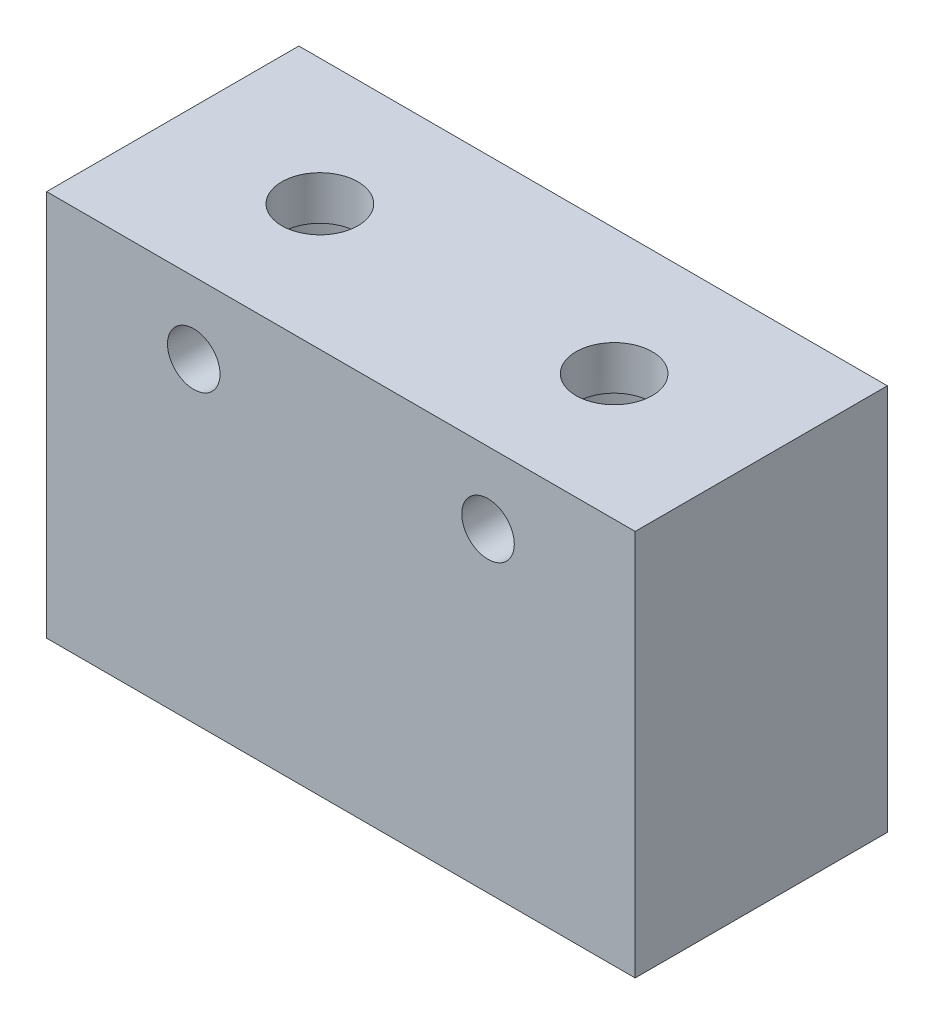
SolidWorks part; units mm, degrees
material "6061 Alloy"
ref_plane "Front Plane" through (0, 0, 0) normal (0, 0, 1) x (1, 0, 0)
ref_plane "Top Plane" through (0, 0, 0) normal (0, 1, 0) x (1, 0, 0)
ref_plane "Right Plane" through (0, 0, 0) normal (1, 0, 0) x (0, 0, -1)
sketch "Sketch1" plane through (0, 0, 0) normal (0, 1, 0) x (1, 0, 0)
  line L1 (-44.45, -19.05) -> (44.45, -19.05)
  line L2 (-44.45, -19.05) -> (-44.45, 19.05)
  line L3 (-44.45, 19.05) -> (44.45, 19.05)
  line L4 (44.45, -19.05) -> (44.45, 19.05)
  line L5 (-44.45, -19.05) -> (44.45, 19.05) construction
  line L6 (-44.45, 19.05) -> (44.45, -19.05) construction
  point P0 (0, 0)
  dimension "D1" = 88.9
  dimension "D2" = 38.1
extrude "Block" add sketch "Sketch1" along normal blind 58.42
sketch "Sketch4" plane through (0, 0, 0) normal (0, -1, 0) x (1, 0, 0)
  line L0 (-22.225, 0) -> (22.225, 0) construction
  point P0 (-22.225, 0)
  point P1 (22.225, 0)
  dimension "D1" = 44.45
hole_wizard "Spring Bores" positions "Sketch6" profile "Sketch7" hole size "1" standard "ANSI Inch"
sketch "Sketch6" plane through (0, 0, 0) normal (0, -1, 0) x (-1, 0, 0)
  point P0 (22.225, 0)
  point P2 (-22.225, 0)
sketch "Sketch7" plane through (-22.225, 0, 0) normal (1, 0, 0) x (0, 0, -1)
  line L0 (0, 0) -> (0, 55.2559)
  line L1 (0, 55.2559) -> (12.7, 47.625)
  line L2 (12.7, 47.625) -> (12.7, 0)
  line L5 (12.7, 0) -> (0, 0)
  line L10 (0, 55.2559) -> (-12.7, 47.625) construction
  line L11 (0, -6.35) -> (0, 107.95) construction
  dimension "Hole Dia." = 25.4
  dimension "Hole Depth" = 47.625
  dimension "Drill Angle" = 118
hole_wizard "1/2-20 Tapped Holes" positions "Sketch9" profile "Sketch8" tap size "1/2-20" standard "ANSI Inch" end condition through all
sketch "Sketch9" plane through (0, 58.42, 0) normal (0, 1, 0) x (1, 0, 0)
  point P0 (-22.225, 0)
  point P3 (22.225, 0)
sketch "Sketch8" plane through (-22.225, 58.42, 0) normal (1, 0, 0) x (0, 0, 1)
  line L0 (0, 0) -> (0, 58.42)
  line L1 (0, 58.42) -> (5.7544, 58.42)
  line L2 (5.7544, 58.42) -> (5.7544, 0)
  line L5 (5.7544, 0) -> (0, 0)
  line L11 (0, -6.35) -> (0, 107.95) construction
  dimension "Thread Major Dia." = 11.5087
  dimension "Thru Tap Drill Depth" = 58.42
hole_wizard "View Holes" positions "Sketch12" profile "Sketch10" hole size "5/16" standard "ANSI Inch" end condition through all
sketch "Sketch12" plane through (0, 0, 19.05) normal (0, 0, 1) x (1, 0, 0)
  line L0 (-9.525, 47.625) -> (-34.925, 47.625) construction
  line L1 (34.925, 47.625) -> (9.525, 47.625) construction
  point P0 (-22.225, 47.625)
  point P4 (22.225, 47.625)
sketch "Sketch10" plane through (-22.225, 47.625, 19.05) normal (1, 0, 0) x (0, -1, 0)
  line L0 (0, 0) -> (0, 38.1)
  line L1 (0, 38.1) -> (3.9687, 38.1)
  line L2 (3.9687, 38.1) -> (3.9687, 0)
  line L5 (3.9687, 0) -> (0, 0)
  line L11 (0, -6.35) -> (0, 107.95) construction
  dimension "Thru Hole Dia." = 7.9375
  dimension "Thru Hole Depth" = 38.1
hole_wizard "#10-32 Tapped Holes" positions "Sketch14" profile "Sketch13" tap size "#10-32" standard "ANSI Inch"
sketch "Sketch14" plane through (0, 0, 0) normal (0, -1, 0) x (-1, 0, 0)
  line L0 (0, 11.1125) -> (0, -11.1125) construction
  line L2 (-36.5125, 11.1125) -> (36.5125, 11.1125) construction
  line L3 (-36.5125, 11.1125) -> (-36.5125, -11.1125) construction
  line L4 (-36.5125, -11.1125) -> (36.5125, -11.1125) construction
  line L5 (36.5125, 11.1125) -> (36.5125, -11.1125) construction
  line L6 (-36.5125, 11.1125) -> (36.5125, -11.1125) construction
  line L7 (-36.5125, -11.1125) -> (36.5125, 11.1125) construction
  line L8 (0, 0) -> (0, -11.1125) construction
  point P0 (0, -11.1125)
  point P2 (0, 11.1125)
  point P9 (36.5125, -11.1125)
  point P11 (36.5125, 11.1125)
  point P13 (-36.5125, 11.1125)
  point P15 (-36.5125, -11.1125)
  dimension "D1" = 22.225
  dimension "D2" = 73.025
sketch "Sketch13" plane through (0, 0, 11.1125) normal (1, 0, 0) x (0, 0, -1)
  line L0 (0, 0) -> (0, 20.2633)
  line L1 (0, 20.2633) -> (2.0193, 19.05)
  line L2 (2.0193, 19.05) -> (2.0193, 0)
  line L5 (2.0193, 0) -> (0, 0)
  line L10 (0, 20.2633) -> (-2.0193, 19.05) construction
  line L11 (0, -6.35) -> (0, 107.95) construction
  dimension "Tap Drill Dia." = 4.0386
  dimension "Tap Drill Depth" = 19.05
  dimension "Drill Angle" = 118
